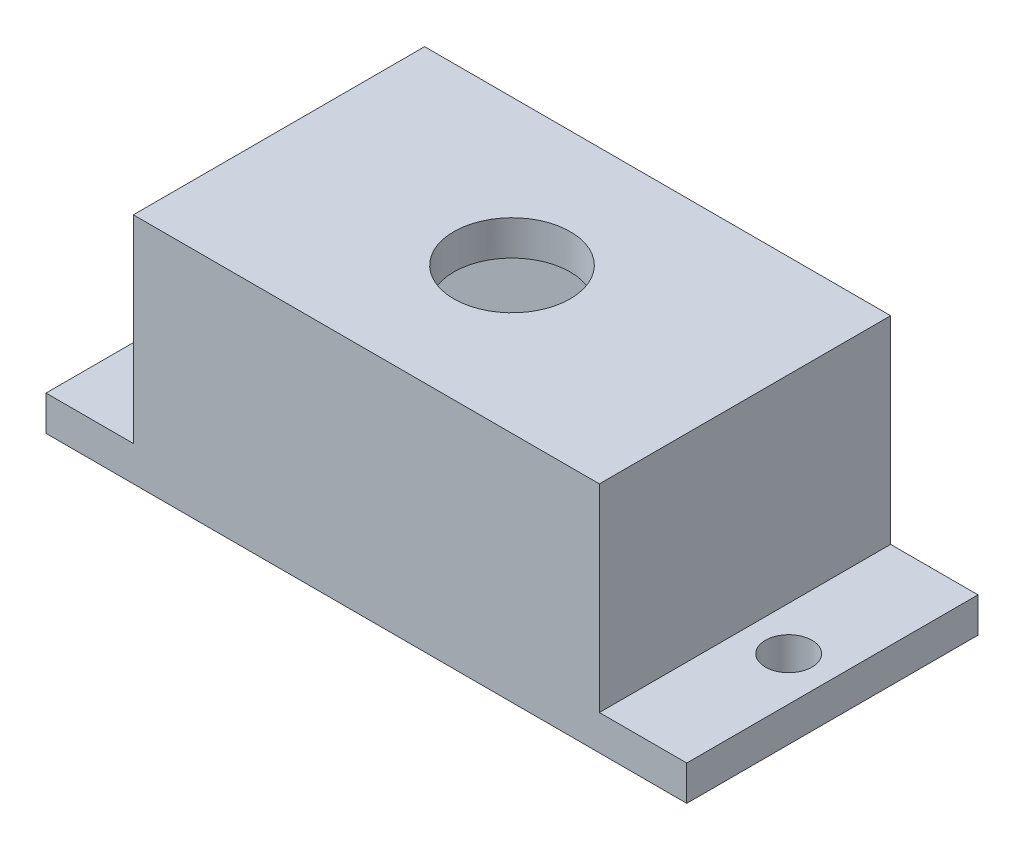
SolidWorks part; units mm, degrees
ref_plane "前视基准面" through (0, 0, 0) normal (0, 0, 1) x (1, 0, 0)
ref_plane "上视基准面" through (0, 0, 0) normal (0, 1, 0) x (1, 0, 0)
ref_plane "右视基准面" through (0, 0, 0) normal (1, 0, 0) x (0, 0, -1)
sketch "草图1" plane through (0, 0, 0) normal (0, 1, 0) x (1, 0, 0)
  line L0 (-55, 25) -> (55, 25)
  line L1 (55, 25) -> (55, -25)
  line L2 (55, -25) -> (-55, -25)
  line L3 (-55, -25) -> (-55, 25)
extrude "凸台-拉伸1" add sketch "草图1" along normal blind 6
ref_plane "基准面1" through (0, 6, 0) normal (0, 1, 0) x (1, 0, 0)
sketch "草图2" plane through (0, 6, 0) normal (0, 1, 0) x (1, 0, 0)
  line L0 (-40, 25) -> (40, 25)
  line L1 (40, 25) -> (40, -25)
  line L2 (40, -25) -> (-40, -25)
  line L3 (-40, -25) -> (-40, 25)
extrude "凸台-拉伸2" add sketch "草图2" along normal blind 34
sketch "草图3" plane through (0, 6, 0) normal (0, 1, 0) x (1, 0, 0)
  line L0 (-35, 20) -> (35, 20)
  line L1 (35, 20) -> (35, -20)
  line L2 (35, -20) -> (-35, -20)
  line L3 (-35, -20) -> (-35, 20)
extrude "切除-拉伸1" cut sketch "草图3" along normal blind 28
ref_plane "基准面2" through (0, 40, 0) normal (0, 1, 0) x (1, 0, 0)
sketch "草图4" plane through (0, 40, 0) normal (0, 1, 0) x (1, 0, 0)
  circle A0 centre (0, 0) radius 10
extrude "切除-拉伸2" cut sketch "草图4" against normal through all
sketch "草图5" plane through (0, 6, 0) normal (0, 1, 0) x (1, 0, 0)
  circle A0 centre (-47.5, 0) radius 4
  circle A1 centre (47.5, 0) radius 4
extrude "切除-拉伸3" cut sketch "草图5" against normal mid plane 222
sketch "草图6" plane through (0, 0, 0) normal (0, 1, 0) x (1, 0, 0)
  line L0 (-35, 20) -> (35, 20)
  line L1 (35, 20) -> (35, -20)
  line L2 (35, -20) -> (-35, -20)
  line L3 (-35, -20) -> (-35, 20)
extrude "切除-拉伸4" cut sketch "草图6" along normal blind 6
